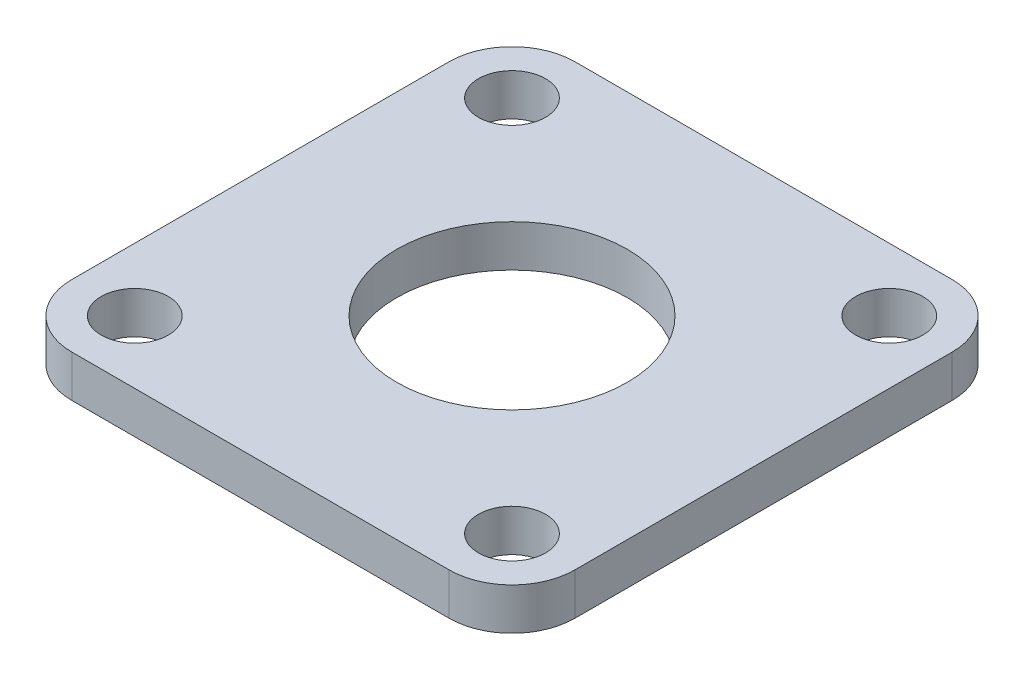
SolidWorks part; units mm, degrees
ref_plane "前视基准面" through (0, 0, 0) normal (0, 0, 1) x (1, 0, 0)
ref_plane "上视基准面" through (0, 0, 0) normal (0, 1, 0) x (1, 0, 0)
ref_plane "右视基准面" through (0, 0, 0) normal (1, 0, 0) x (0, 0, -1)
sketch "草图1" plane through (0, 0, 0) normal (0, 1, 0) x (1, 0, 0)
  line L1 (-12, -12) -> (12, -12)
  line L2 (-12, -12) -> (-12, 12)
  line L3 (-12, 12) -> (12, 12)
  line L4 (12, -12) -> (12, 12)
  line L5 (-12, -12) -> (12, 12) construction
  line L6 (-12, 12) -> (12, -12) construction
  point P0 (0, 0)
  dimension "D1" = 24
  dimension "D2" = 24
extrude "凸台-拉伸1" add sketch "草图1" along normal blind 2
fillet "圆角1" radius 3 4 edges at (-12, 1, 12) (-12, 1, -12) (12, 1, -12) (12, 1, 12)
sketch "草图2" plane through (0, 2, 0) normal (0, 1, 0) x (1, 0, 0)
  line L1 (-9, -9) -> (9, -9) construction
  line L2 (-9, -9) -> (-9, 9) construction
  line L3 (-9, 9) -> (9, 9) construction
  line L4 (9, -9) -> (9, 9) construction
  line L5 (-9, -9) -> (9, 9) construction
  line L6 (-9, 9) -> (9, -9) construction
  circle A0 centre (-9, 9) radius 1.6
  circle A1 centre (9, 9) radius 1.6
  circle A2 centre (9, -9) radius 1.6
  circle A3 centre (-9, -9) radius 1.6
  point P0 (0, 0)
  dimension "D3" = 3.2
  dimension "D4" = 3.2
  dimension "D5" = 3.2
  dimension "D6" = 3.2
  dimension "D1" = 18
  dimension "D2" = 18
extrude "切除-拉伸1" cut sketch "草图2" against normal blind 2
sketch "草图3" plane through (0, 2, 0) normal (0, 1, 0) x (1, 0, 0)
  circle A0 centre (0, 0) radius 5.5
  dimension "D1" = 11
extrude "切除-拉伸2" cut sketch "草图3" against normal blind 2
